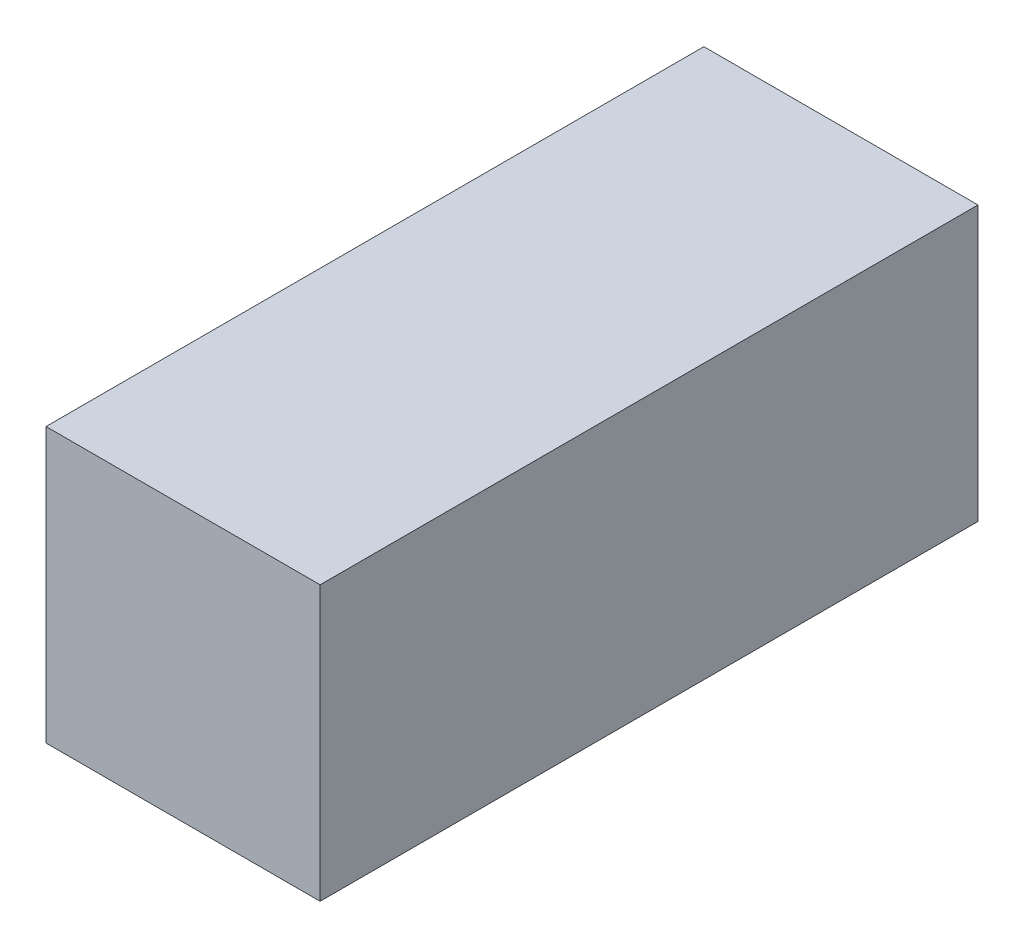
SolidWorks part; units mm, degrees
ref_plane "Спереди" through (0, 0, 0) normal (0, 0, 1) x (1, 0, 0)
ref_plane "Сверху" through (0, 0, 0) normal (0, 1, 0) x (1, 0, 0)
ref_plane "Справа" through (0, 0, 0) normal (1, 0, 0) x (0, 0, -1)
sketch "Эскиз1" plane through (0, 0, 0) normal (0, 0, 1) x (1, 0, 0)
  line L0 (5.5, -2.5) -> (10.5, -2.5)
  line L1 (10.5, -2.5) -> (10.5, 2.5)
  line L2 (10.5, 2.5) -> (5.5, 2.5)
  line L3 (5.5, 2.5) -> (5.5, -2.5)
extrude "Reaction_key" add sketch "Эскиз1" along normal blind 12 from offset 29.75
